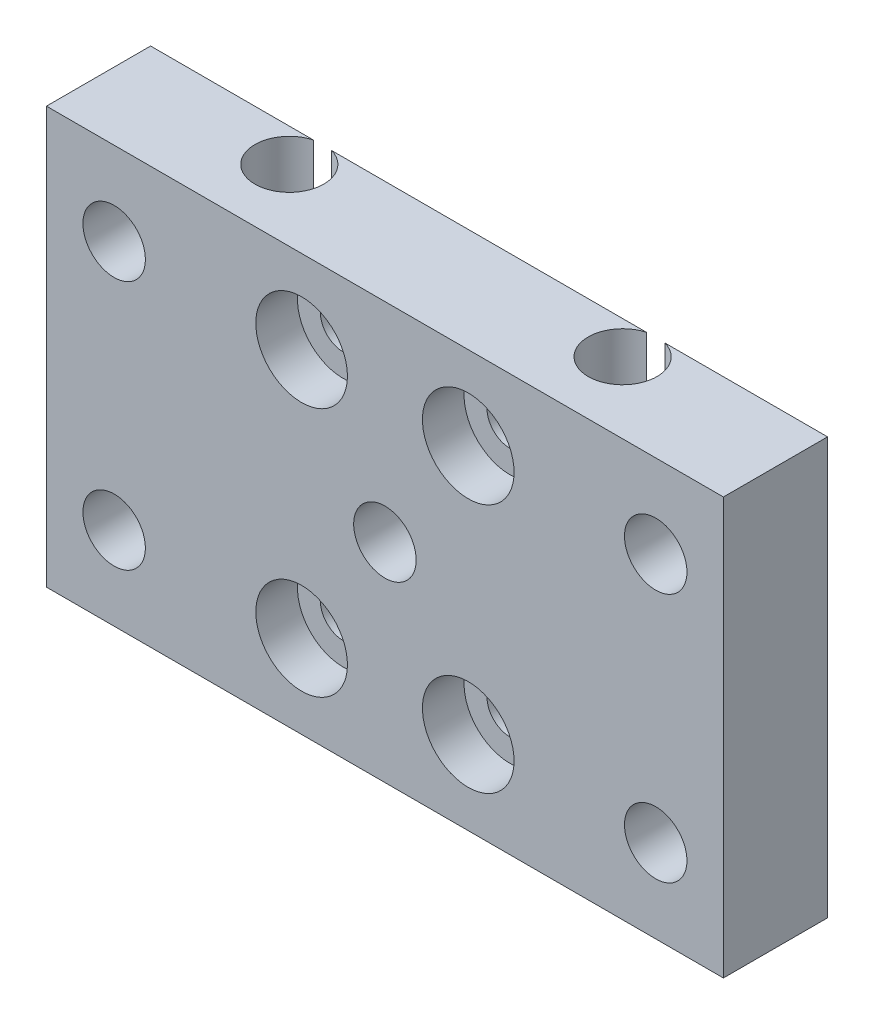
SolidWorks part; units mm, degrees
ref_plane "Front Plane" through (0, 0, 0) normal (0, 0, 1) x (1, 0, 0)
ref_plane "Top Plane" through (0, 0, 0) normal (0, 1, 0) x (1, 0, 0)
ref_plane "Right Plane" through (0, 0, 0) normal (1, 0, 0) x (0, 0, -1)
sketch "Sketch1" plane through (0, 0, 0) normal (0, 0, 1) x (1, 0, 0)
  line L1 (-11.25, 10) -> (11.25, 10)
  line L2 (-11.25, 10) -> (-11.25, -10)
  line L3 (-11.25, -10) -> (11.25, -10)
  line L4 (11.25, 10) -> (11.25, -10)
  line L5 (0, -10) -> (0, 10) construction
  line L6 (-11.25, 0) -> (11.25, 0) construction
  point P0 (0, 0)
  dimension "D1" = 20
  dimension "D2" = 22.5
extrude "Boss-Extrude1" add sketch "Sketch1" along normal blind 5
hole_wizard "CBORE for M2 SHCS1" positions "Sketch2" profile "Sketch3" counterbore size "M2" standard "ANSI Metric" end condition through all
sketch "Sketch2" plane through (0, 0, 5) normal (0, 0, 1) x (1, 0, 0)
  line L1 (-4, -6) -> (4, -6)
  line L2 (-4, -6) -> (-4, 6)
  line L3 (-4, 6) -> (4, 6)
  line L4 (4, -6) -> (4, 6)
  line L5 (0, 6) -> (0, -6) construction
  line L6 (-4, 0) -> (4, 0) construction
  point P2 (4, 6)
  point P909 (-4, -6)
  point P910 (-4, 6)
  point P924 (4, -6)
  dimension "D1" = 8
  dimension "D2" = 12
sketch "Sketch3" plane through (4, 6, 5) normal (1, 0, 0) x (0, -1, 0)
  line L0 (0, 0) -> (0, 5)
  line L1 (0, 5) -> (1.1, 5)
  line L3 (1.1, 5) -> (1.1, 2)
  line L4 (1.1, 2) -> (2.2, 2)
  line L5 (2.2, 2) -> (2.2, 0)
  line L7 (2.2, 0) -> (0, 0)
  line L11 (0, -6.35) -> (0, 107.95) construction
  dimension "Thru Hole Dia." = 2.2
  dimension "Thru Hole Depth" = 5
  dimension "C'Bore Dia." = 4.4
  dimension "C'Bore Depth" = 2
hole_wizard "Tap Drill for M2x0.4 Tap1" positions "Sketch5" profile "Sketch6" hole size "M2x0.4" standard "ANSI Metric"
sketch "Sketch5" plane through (0, 10, 0) normal (0, 1, 0) x (1, 0, 0)
  line L0 (0, 0) -> (0, -5) construction
  line L1 (11.25, -5) -> (-11.25, -5) construction
  line L3 (0, -1.59) -> (-8, -1.59) construction
  line L4 (11.25, 0) -> (-11.25, 0) construction
  point P9 (-8, -1.59)
  point P16 (8, -1.59)
  point P17 (0, 0)
  dimension "D1" = 8
  dimension "D2" = 1.59
sketch "Sketch6" plane through (8, 10, 1.59) normal (1, 0, 0) x (0, 0, 1)
  line L0 (0, 0) -> (0, 7)
  line L1 (0, 7) -> (1.65, 6.0086)
  line L2 (1.65, 6.0086) -> (1.65, 0)
  line L5 (1.65, 0) -> (0, 0)
  line L10 (0, 7) -> (-1.65, 6.0086) construction
  line L11 (0, -6.35) -> (0, 107.95) construction
  dimension "Hole Dia." = 3.3
  dimension "Hole Depth" = 7
  dimension "Drill Angle" = 118
sketch "Sketch9" plane through (0, 0, 5) normal (0, 0, 1) x (1, 0, 0)
  line L0 (0, 0) -> (0, 16.5959) construction
  line L1 (-11.25, 10) -> (-16.25, 10)
  line L2 (-11.25, 10) -> (-11.25, -10)
  line L3 (-11.25, -10) -> (-16.25, -10)
  line L4 (-16.25, 10) -> (-16.25, -10)
  line L5 (-13.75, -10) -> (-13.75, 10) construction
  line L6 (-11.25, 0) -> (-16.25, 0) construction
  line L7 (11.25, -10) -> (16.25, -10)
  line L8 (16.25, 10) -> (16.25, -10)
  line L9 (11.25, 10) -> (16.25, 10)
  line L10 (11.25, 10) -> (11.25, -10)
  point P6 (-11.25, -10)
  point P180 (-13.75, 0)
  dimension "D1" = 5
extrude "Boss-Extrude2" add sketch "Sketch9" against normal up to surface (5 mm away) up to face at (5.1, 6, 0)
hole_wizard "Ø3.0mm Dowel Hole1" positions "Sketch10" profile "Sketch11" hole size "Ø3.0" standard "ANSI Metric" end condition through all
sketch "Sketch10" plane through (0, 0, 5) normal (0, 0, 1) x (1, 0, 0)
  line L0 (0, 0) -> (-13, 0) construction
  line L1 (-13, 0) -> (-13, 6) construction
  line L3 (0, 0) -> (0, 4.1348) construction
  point P1 (0, 0)
  point P5 (-13, 6)
  point P18 (0, 0)
  point P19 (-13, -6)
  point P20 (0, 0)
  point P21 (13, -6)
  point P22 (13, 6)
  dimension "D1" = 13
  dimension "D2" = 6
sketch "Sketch11" plane through (0, 0, 5) normal (1, 0, 0) x (0, -1, 0)
  line L0 (0, 0) -> (0, 5)
  line L1 (0, 5) -> (1.5, 5)
  line L2 (1.5, 5) -> (1.5, 0)
  line L5 (1.5, 0) -> (0, 0)
  line L11 (0, -6.35) -> (0, 107.95) construction
  dimension "Thru Hole Dia." = 3
  dimension "Thru Hole Depth" = 5
sketch "Sketch12" plane through (0, 0, 0) normal (0, 0, -1) x (-1, 0, 0)
  line L1 (-13, 2.8246) -> (-10.25, 4.4123)
  line L2 (-10.25, 4.4123) -> (-10.25, 7.5877)
  line L3 (-10.25, 7.5877) -> (-13, 9.1754)
  line L4 (-13, 9.1754) -> (-15.75, 7.5877)
  line L5 (-15.75, 7.5877) -> (-15.75, 4.4123)
  line L6 (-15.75, 4.4123) -> (-13, 2.8246)
  line L7 (0, -3.1754) -> (2.75, -1.5877)
  line L8 (2.75, -1.5877) -> (2.75, 1.5877)
  line L9 (2.75, 1.5877) -> (0, 3.1754)
  line L10 (0, 3.1754) -> (-2.75, 1.5877)
  line L11 (-2.75, 1.5877) -> (-2.75, -1.5877)
  line L12 (-2.75, -1.5877) -> (0, -3.1754)
  line L13 (13, 2.8246) -> (15.75, 4.4123)
  line L14 (15.75, 4.4123) -> (15.75, 7.5877)
  line L15 (15.75, 7.5877) -> (13, 9.1754)
  line L16 (13, 9.1754) -> (10.25, 7.5877)
  line L17 (10.25, 7.5877) -> (10.25, 4.4123)
  line L18 (10.25, 4.4123) -> (13, 2.8246)
  line L19 (13, -2.8246) -> (10.25, -4.4123)
  line L20 (10.25, -4.4123) -> (10.25, -7.5877)
  line L21 (10.25, -7.5877) -> (13, -9.1754)
  line L22 (13, -9.1754) -> (15.75, -7.5877)
  line L23 (15.75, -7.5877) -> (15.75, -4.4123)
  line L24 (15.75, -4.4123) -> (13, -2.8246)
  line L25 (-13, -2.8246) -> (-15.75, -4.4123)
  line L26 (-15.75, -4.4123) -> (-15.75, -7.5877)
  line L27 (-15.75, -7.5877) -> (-13, -9.1754)
  line L28 (-13, -9.1754) -> (-10.25, -7.5877)
  line L29 (-10.25, -7.5877) -> (-10.25, -4.4123)
  line L30 (-10.25, -4.4123) -> (-13, -2.8246)
  circle A0 centre (-13, 6) radius 2.75 construction
  circle A1 centre (0, 0) radius 2.75 construction
  circle A2 centre (13, 6) radius 2.75 construction
  circle A3 centre (13, -6) radius 2.75 construction
  circle A4 centre (-13, -6) radius 2.75 construction
  dimension "D1" = 5.5
extrude "Cut-Extrude1" cut sketch "Sketch12" against normal blind 2.4
